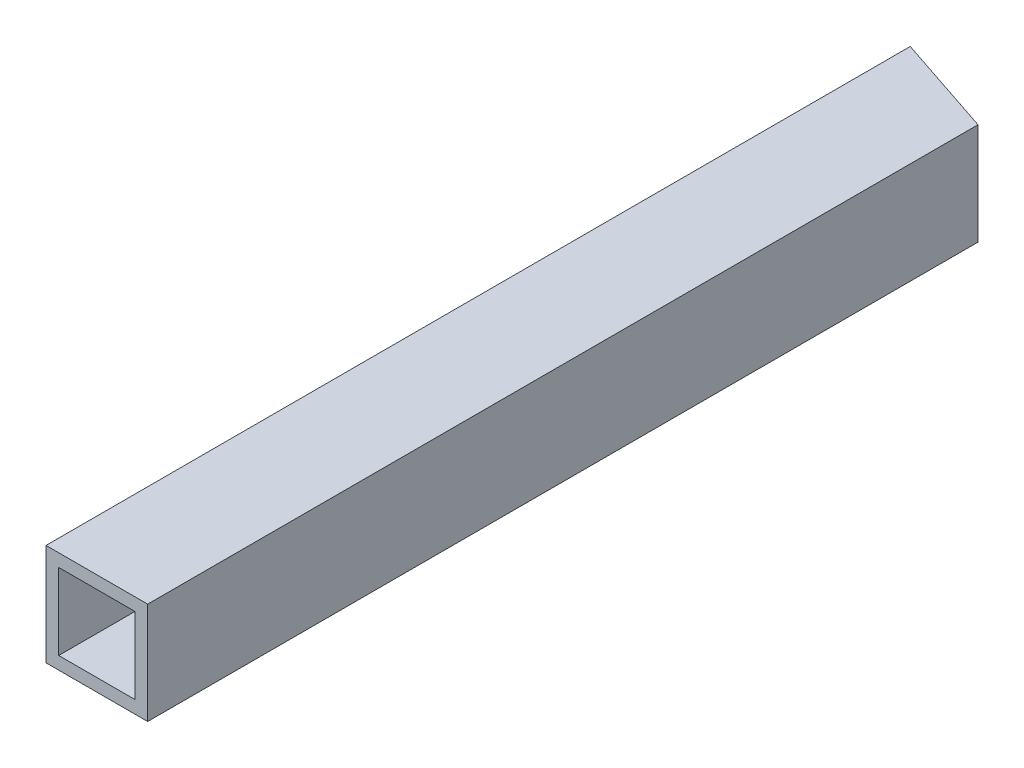
SolidWorks part; units mm, degrees
ref_plane "Front Plane" through (0, 0, 0) normal (0, 0, 1) x (1, 0, 0)
ref_plane "Top Plane" through (0, 0, 0) normal (0, 1, 0) x (1, 0, 0)
ref_plane "Right Plane" through (0, 0, 0) normal (1, 0, 0) x (0, 0, -1)
sketch "Sketch1" plane through (0, 0, 0) normal (0, 0, 1) x (1, 0, 0)
  line L1 (0, 0) -> (25.4, 0)
  line L2 (0, 0) -> (0, 25.4)
  line L3 (0, 25.4) -> (25.4, 25.4)
  line L4 (25.4, 0) -> (25.4, 25.4)
  line L5 (3.175, 22.225) -> (22.225, 22.225)
  line L6 (3.175, 22.225) -> (3.175, 3.175)
  line L7 (3.175, 3.175) -> (22.225, 3.175)
  line L8 (22.225, 22.225) -> (22.225, 3.175)
  dimension "D1" = 25.4
  dimension "D2" = 25.4
  dimension "D3" = 3.175
  dimension "D4" = 3.175
  dimension "D5" = 3.175
  dimension "D6" = 3.175
extrude "Boss-Extrude1" add sketch "Sketch1" along normal blind 215.9
sketch "Sketch2" plane through (0, 25.4, 0) normal (0, 1, 0) x (1, 0, 0)
  line L0 (0, 0) -> (25.4, -8.4692)
  line L1 (25.4, -215.9) -> (25.4, 0) construction
  line L2 (25.4, -8.4692) -> (25.4, 0)
  line L3 (25.4, 0) -> (0, 0)
  dimension "D1" = 18.44
extrude "Cut-Extrude1" cut sketch "Sketch2" against normal through all
